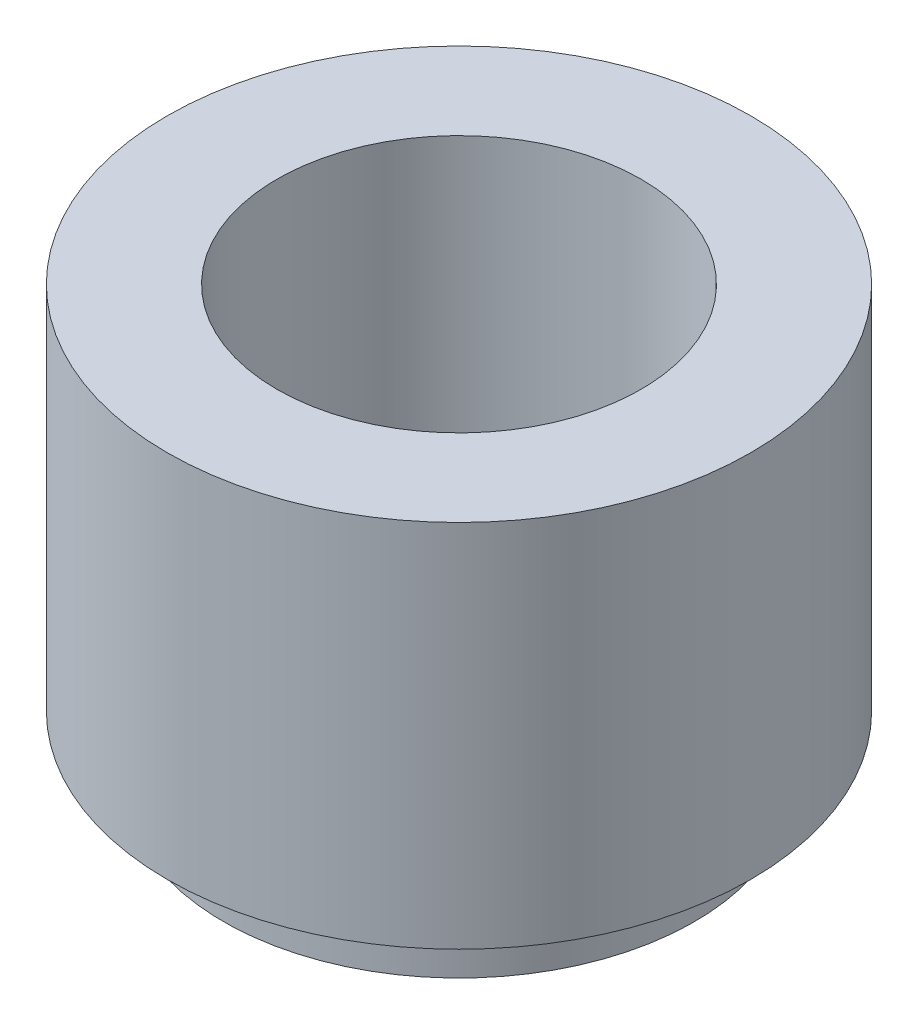
SolidWorks part; units mm, degrees
material "AISI 304"
ref_plane "Front Plane" through (0, 0, 0) normal (0, 0, 1) x (1, 0, 0)
ref_plane "Top Plane" through (0, 0, 0) normal (0, 1, 0) x (1, 0, 0)
ref_plane "Right Plane" through (0, 0, 0) normal (1, 0, 0) x (0, 0, -1)
sketch "Sketch1" plane through (0, 0, 0) normal (0, 1, 0) x (1, 0, 0)
  circle A0 centre (0, 0) radius 9.525
  dimension "D1" = 19.05
extrude "Boss-Extrude1" add sketch "Sketch1" along normal blind 5.715
sketch "Sketch2" plane through (0, 0, 0) normal (0, -1, 0) x (1, 0, 0)
  line L1 (0, -10.9985) -> (9.525, -5.4993)
  line L2 (9.525, -5.4993) -> (9.525, 5.4993)
  line L3 (9.525, 5.4993) -> (0, 10.9985)
  line L4 (0, 10.9985) -> (-9.525, 5.4993)
  line L5 (-9.525, 5.4993) -> (-9.525, -5.4993)
  line L6 (-9.525, -5.4993) -> (0, -10.9985)
  circle A0 centre (0, 0) radius 9.525 construction
  circle A2 centre (0, 0) radius 9.525 construction
  point P11 (0, 0)
extrude "Boss-Extrude2" add sketch "Sketch2" along normal blind 6.35
sketch "Sketch3" plane through (0, -6.35, 0) normal (0, -1, 0) x (1, 0, 0)
  circle A0 centre (0, 0) radius 7.9375
  dimension "D1" = 15.875
extrude "Boss-Extrude3" add sketch "Sketch3" along normal blind 1.0583
sketch "Sketch4" plane through (0, -7.4083, 0) normal (0, -1, 0) x (1, 0, 0)
  circle A0 centre (0, 0) radius 7.6835
  circle A1 centre (0, 0) radius 7.9375 construction
  dimension "D1" = 0.254
extrude "Boss-Extrude4" add sketch "Sketch4" along normal blind 1.0583
hole_wizard "1/4-18 NPSM Tapped Hole2" positions "Sketch9" profile "Sketch10" tap size "1/4-18 NPSM" standard "ANSI Inch" end condition through all
sketch "Sketch9" plane through (0, 5.715, 0) normal (0, 1, 0) x (1, 0, 0)
  point P0 (0, 0)
sketch "Sketch10" plane through (0, 5.715, 0) normal (1, 0, 0) x (0, 0, 1)
  line L0 (0, 0) -> (0, 14.1817)
  line L1 (0, 14.1817) -> (5.9436, 14.1817)
  line L2 (5.9436, 14.1817) -> (5.9436, 0)
  line L5 (5.9436, 0) -> (0, 0)
  line L11 (0, -6.35) -> (0, 107.95) construction
  dimension "Thru Tap Drill Dia." = 11.8872
  dimension "Thru Tap Drill Depth" = 14.1817
cosmetic thread "Hole Thread1" parameters "D2"=13.3604
sketch "Sketch11" plane through (0, 5.715, 0) normal (0, 1, 0) x (1, 0, 0)
  circle A0 centre (0, 0) radius 10.9985
  circle A1 centre (0, 0) radius 9.525
  circle A2 centre (0, 0) radius 9.525 construction
extrude "Cut-Extrude1" cut sketch "Sketch11" against normal through all
